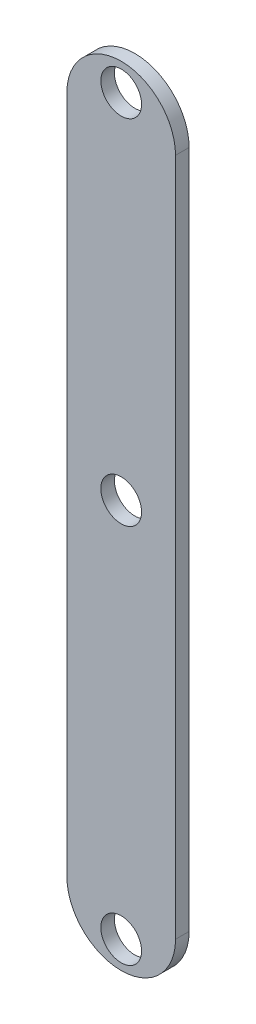
SolidWorks part; units mm, degrees
ref_plane "Front Plane" through (0, 0, 0) normal (0, 0, 1) x (1, 0, 0)
ref_plane "Top Plane" through (0, 0, 0) normal (0, 1, 0) x (1, 0, 0)
ref_plane "Right Plane" through (0, 0, 0) normal (1, 0, 0) x (0, 0, -1)
sketch "Sketch1" plane through (0, 0, 0) normal (0, 0, 1) x (1, 0, 0)
  line L0 (0, 0) -> (0, 250) construction
  line L1 (-20, 0) -> (-20, 250)
  line L2 (20, 0) -> (20, 250)
  arc A0 (-20, 0) -> (20, 0) centre (0, 0) ccw
  arc A1 (20, 250) -> (-20, 250) centre (0, 250) ccw
  point P3 (0, 125)
  dimension "D2" = 250
  dimension "D1" = 40
extrude "Boss-Extrude1" add sketch "Sketch1" along normal blind 5
sketch "Sketch3" plane through (0, 0, 0) normal (0, 0, 1) x (1, 0, 0)
  line L0 (-44.4937, 250) -> (44.4937, 250) construction
  line L1 (0, 250) -> (0, 270) construction
  line L2 (-112.6735, 125) -> (72.6735, 125) construction
  arc A2 (20, 250) -> (-20, 250) centre (0, 250) ccw construction
  circle A3 centre (0, 260) radius 7.5
  circle A4 centre (0, -10) radius 7.5
  arc A5 (-20, 0) -> (20, 0) centre (0, 0) ccw construction
  point P8 (0, 250)
  point P16 (-20, 125)
  dimension "D1" = 15
  dimension "D3" = 10
  dimension "D2" = 0
extrude "Cut-Extrude4" cut sketch "Sketch3" against normal through all and the other way through all
sketch "Sketch5" plane through (0, 0, 5) normal (0, 0, 1) x (1, 0, 0)
  line L0 (0, 336.2947) -> (0, -76.3463) construction
  circle A0 centre (0, 129.9742) radius 7.5
  point P3 (0, 129.9742)
  point P4 (0, 129.9742)
  dimension "D1" = 15
extrude "Cut-Extrude5" cut sketch "Sketch5" against normal through all both and the other way through all
